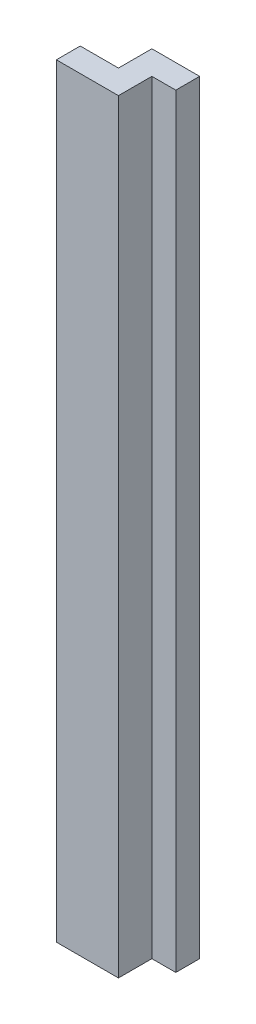
SolidWorks part; units mm, degrees
ref_plane "Front Plane" through (0, 0, 0) normal (0, 0, 1) x (1, 0, 0)
ref_plane "Top Plane" through (0, 0, 0) normal (0, 1, 0) x (1, 0, 0)
ref_plane "Right Plane" through (0, 0, 0) normal (1, 0, 0) x (0, 0, -1)
sketch "Sketch1" plane through (0, 0, 0) normal (0, 1, 0) x (1, 0, 0)
  line L1 (0, 0) -> (8, 0)
  line L2 (0, 0) -> (0, -5)
  line L3 (0, -5) -> (8, -5)
  line L5 (8, -5) -> (13, -5)
  line L6 (8, 0) -> (8, 7)
  line L7 (8, 7) -> (13, 7)
  line L8 (13, -5) -> (13, 7)
  dimension "D1" = 8
  dimension "D2" = 5
  dimension "D3" = 5
  dimension "D4" = 7
extrude "Boss-Extrude1" add sketch "Sketch1" along normal blind 160
sketch "Sketch2" plane through (13, 0, 0) normal (1, 0, 0) x (0, 0, -1)
  line L0 (7, 160) -> (2, 160)
  line L2 (7, 160) -> (7, 0)
  line L3 (7, 0) -> (2, 0)
  line L5 (-5, 160) -> (7, 160) construction
  line L6 (2, 160) -> (2, 0)
  dimension "D1" = 5
extrude "Boss-Extrude2" add sketch "Sketch2" along normal blind 5
